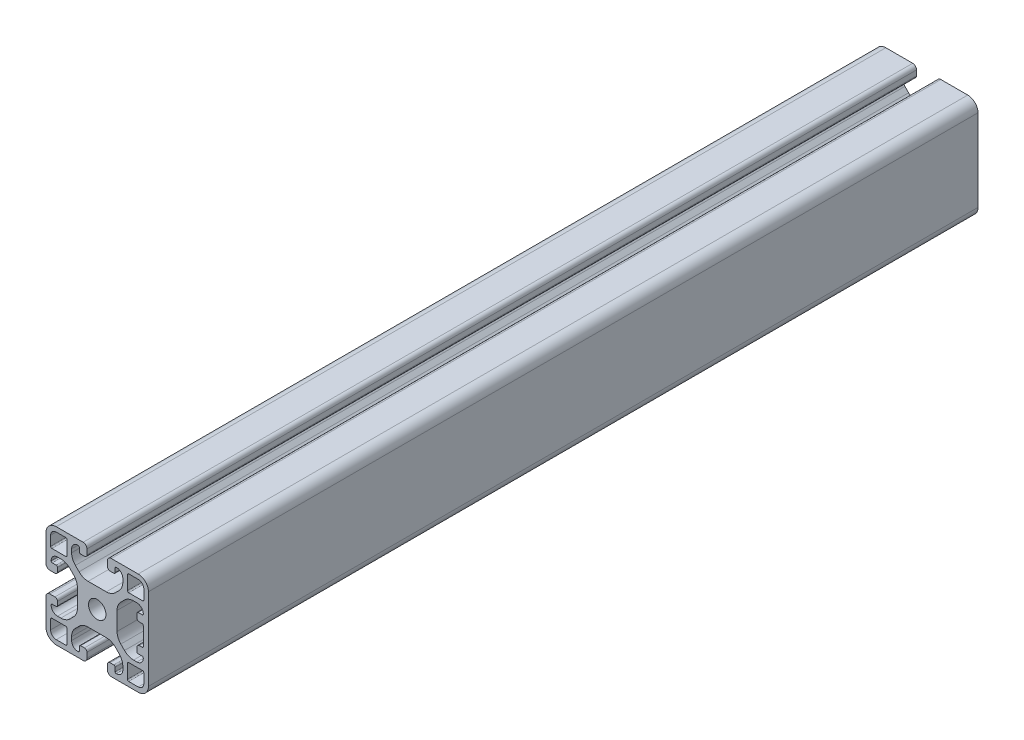
SolidWorks part; units mm, degrees
ref_plane "Piano frontale" through (0, 0, 0) normal (0, 0, 1) x (1, 0, 0)
ref_plane "Piano superiore" through (0, 0, 0) normal (0, 1, 0) x (1, 0, 0)
ref_plane "Piano destro" through (0, 0, 0) normal (1, 0, 0) x (0, 0, -1)
ref_plane "Piano1" through (0, 0, -340) normal (0, 0, -1) x (-1, 0, 0)
sketch "Schizzo1" plane through (0, 0, -340) normal (0, 0, -1) x (-1, 0, 0)
  line L0 (-12.3, -18.2) -> (-16, -18.2)
  line L1 (-18.2, -16) -> (-18.2, -12.3)
  line L2 (-17.7, -11.8) -> (-12.3, -11.8)
  line L3 (-11.8, -12.3) -> (-11.8, -17.7)
  line L4 (-11.8, 17.7) -> (-11.8, 12.3)
  line L5 (-12.3, 11.8) -> (-17.7, 11.8)
  line L6 (-18.2, 12.3) -> (-18.2, 16)
  line L7 (-16, 18.2) -> (-12.3, 18.2)
  line L8 (18.2, 16) -> (18.2, 12.3)
  line L9 (17.7, 11.8) -> (12.3, 11.8)
  line L10 (11.8, 12.3) -> (11.8, 17.7)
  line L11 (12.3, 18.2) -> (16, 18.2)
  line L12 (6.5, -15.5) -> (5, -15.5)
  line L13 (4, -16.5) -> (4, -18.5)
  line L14 (5.5, -20) -> (16, -20)
  line L15 (20, -16) -> (20, -5.5)
  line L16 (18.5, -4) -> (16.5, -4)
  line L17 (15.5, -5) -> (15.5, -6.5)
  line L18 (16, -7) -> (17.55, -7)
  line L19 (18, -7.45) -> (18, -7.5)
  line L20 (15.5, -10) -> (14.1924, -10)
  line L21 (10.6569, -8.5355) -> (9.2145, -7.0931)
  line L22 (7.75, -3.5576) -> (7.75, 3.5576)
  line L23 (9.2145, 7.0931) -> (10.6569, 8.5355)
  line L24 (14.1924, 10) -> (15.5, 10)
  line L25 (18, 7.5) -> (18, 7.45)
  line L26 (17.55, 7) -> (16, 7)
  line L27 (15.5, 6.5) -> (15.5, 5)
  line L28 (16.5, 4) -> (18.5, 4)
  line L29 (20, 5.5) -> (20, 16)
  line L30 (16, 20) -> (5.5, 20)
  line L31 (4, 18.5) -> (4, 16.5)
  line L32 (5, 15.5) -> (6.5, 15.5)
  line L33 (7, 16) -> (7, 17.55)
  line L34 (7.45, 18) -> (7.5, 18)
  line L35 (10, 15.5) -> (10, 14.1924)
  line L36 (8.5355, 10.6569) -> (7.0931, 9.2145)
  line L37 (3.5576, 7.75) -> (-3.5576, 7.75)
  line L38 (-7.0931, 9.2145) -> (-8.5355, 10.6569)
  line L39 (-10, 14.1924) -> (-10, 15.5)
  line L40 (-7.5, 18) -> (-7.45, 18)
  line L41 (-7, 17.55) -> (-7, 16)
  line L42 (-6.5, 15.5) -> (-5, 15.5)
  line L43 (-4, 16.5) -> (-4, 18.5)
  line L44 (-5.5, 20) -> (-16, 20)
  line L45 (-20, 16) -> (-20, -16)
  line L46 (-16, -20) -> (-5.5, -20)
  line L47 (-4, -18.5) -> (-4, -16.5)
  line L48 (-5, -15.5) -> (-6.5, -15.5)
  line L49 (-7, -16) -> (-7, -17.55)
  line L50 (-7.45, -18) -> (-7.5, -18)
  line L51 (-10, -15.5) -> (-10, -14.1924)
  line L52 (-8.5355, -10.6569) -> (-7.0931, -9.2145)
  line L53 (-3.5576, -7.75) -> (3.5576, -7.75)
  line L54 (7.0931, -9.2145) -> (8.5355, -10.6569)
  line L55 (10, -14.1924) -> (10, -15.5)
  line L56 (7.5, -18) -> (7.45, -18)
  line L57 (7, -17.55) -> (7, -16)
  line L58 (18.2, -12.3) -> (18.2, -16)
  line L59 (16, -18.2) -> (12.3, -18.2)
  line L60 (11.8, -17.7) -> (11.8, -12.3)
  line L61 (12.3, -11.8) -> (17.7, -11.8)
  line L62 (-16, 7) -> (-17.5, 7)
  line L63 (-15.5, 10) -> (-14.1924, 10)
  line L64 (-10.6569, 8.5355) -> (-9.2145, 7.0931)
  line L65 (-7.75, 3.5576) -> (-7.75, -3.5576)
  line L66 (-9.2145, -7.0931) -> (-10.6569, -8.5355)
  line L67 (-14.1924, -10) -> (-15.5, -10)
  line L68 (-17.5, -7) -> (-16, -7)
  line L69 (-15.5, -6.5) -> (-15.5, -5)
  line L70 (-16.5, -4) -> (-17.5, -4)
  line L71 (-18, -3.5) -> (-18, 3.5)
  line L72 (-17.5, 4) -> (-16.5, 4)
  line L73 (-15.5, 5) -> (-15.5, 6.5)
  arc A0 (-16, -18.2) -> (-18.2, -16) centre (-16, -16) cw
  arc A1 (-18.2, -12.3) -> (-17.7, -11.8) centre (-17.7, -12.3) cw
  arc A2 (-12.3, -11.8) -> (-11.8, -12.3) centre (-12.3, -12.3) cw
  arc A3 (-11.8, -17.7) -> (-12.3, -18.2) centre (-12.3, -17.7) cw
  arc A4 (-12.3, 18.2) -> (-11.8, 17.7) centre (-12.3, 17.7) cw
  arc A5 (-11.8, 12.3) -> (-12.3, 11.8) centre (-12.3, 12.3) cw
  arc A6 (-17.7, 11.8) -> (-18.2, 12.3) centre (-17.7, 12.3) cw
  arc A7 (-18.2, 16) -> (-16, 18.2) centre (-16, 16) cw
  arc A8 (16, 18.2) -> (18.2, 16) centre (16, 16) cw
  arc A9 (18.2, 12.3) -> (17.7, 11.8) centre (17.7, 12.3) cw
  arc A10 (12.3, 11.8) -> (11.8, 12.3) centre (12.3, 12.3) cw
  arc A11 (11.8, 17.7) -> (12.3, 18.2) centre (12.3, 17.7) cw
  arc A12 (5, -15.5) -> (4, -16.5) centre (5, -16.5) ccw
  arc A13 (4, -18.5) -> (5.5, -20) centre (5.5, -18.5) ccw
  arc A14 (16, -20) -> (20, -16) centre (16, -16) ccw
  arc A15 (20, -5.5) -> (18.5, -4) centre (18.5, -5.5) ccw
  arc A16 (16.5, -4) -> (15.5, -5) centre (16.5, -5) ccw
  arc A17 (15.5, -6.5) -> (16, -7) centre (16, -6.5) ccw
  arc A18 (17.55, -7) -> (18, -7.45) centre (17.55, -7.45) cw
  arc A19 (18, -7.5) -> (15.5, -10) centre (15.5, -7.5) cw
  arc A20 (14.1924, -10) -> (10.6569, -8.5355) centre (14.1924, -5) cw
  arc A21 (9.2145, -7.0931) -> (7.75, -3.5576) centre (12.75, -3.5576) cw
  arc A22 (7.75, 3.5576) -> (9.2145, 7.0931) centre (12.75, 3.5576) cw
  arc A23 (10.6569, 8.5355) -> (14.1924, 10) centre (14.1924, 5) cw
  arc A24 (15.5, 10) -> (18, 7.5) centre (15.5, 7.5) cw
  arc A25 (18, 7.45) -> (17.55, 7) centre (17.55, 7.45) cw
  arc A26 (16, 7) -> (15.5, 6.5) centre (16, 6.5) ccw
  arc A27 (15.5, 5) -> (16.5, 4) centre (16.5, 5) ccw
  arc A28 (18.5, 4) -> (20, 5.5) centre (18.5, 5.5) ccw
  arc A29 (20, 16) -> (16, 20) centre (16, 16) ccw
  arc A30 (5.5, 20) -> (4, 18.5) centre (5.5, 18.5) ccw
  arc A31 (4, 16.5) -> (5, 15.5) centre (5, 16.5) ccw
  arc A32 (6.5, 15.5) -> (7, 16) centre (6.5, 16) ccw
  arc A33 (7, 17.55) -> (7.45, 18) centre (7.45, 17.55) cw
  arc A34 (7.5, 18) -> (10, 15.5) centre (7.5, 15.5) cw
  arc A35 (10, 14.1924) -> (8.5355, 10.6569) centre (5, 14.1924) cw
  arc A36 (7.0931, 9.2145) -> (3.5576, 7.75) centre (3.5576, 12.75) cw
  arc A37 (-3.5576, 7.75) -> (-7.0931, 9.2145) centre (-3.5576, 12.75) cw
  arc A38 (-8.5355, 10.6569) -> (-10, 14.1924) centre (-5, 14.1924) cw
  arc A39 (-10, 15.5) -> (-7.5, 18) centre (-7.5, 15.5) cw
  arc A40 (-7.45, 18) -> (-7, 17.55) centre (-7.45, 17.55) cw
  arc A41 (-7, 16) -> (-6.5, 15.5) centre (-6.5, 16) ccw
  arc A42 (-5, 15.5) -> (-4, 16.5) centre (-5, 16.5) ccw
  arc A43 (-4, 18.5) -> (-5.5, 20) centre (-5.5, 18.5) ccw
  arc A44 (-16, 20) -> (-20, 16) centre (-16, 16) ccw
  arc A45 (-20, -16) -> (-16, -20) centre (-16, -16) ccw
  arc A46 (-5.5, -20) -> (-4, -18.5) centre (-5.5, -18.5) ccw
  arc A47 (-4, -16.5) -> (-5, -15.5) centre (-5, -16.5) ccw
  arc A48 (-6.5, -15.5) -> (-7, -16) centre (-6.5, -16) ccw
  arc A49 (-7, -17.55) -> (-7.45, -18) centre (-7.45, -17.55) cw
  arc A50 (-7.5, -18) -> (-10, -15.5) centre (-7.5, -15.5) cw
  arc A51 (-10, -14.1924) -> (-8.5355, -10.6569) centre (-5, -14.1924) cw
  arc A52 (-7.0931, -9.2145) -> (-3.5576, -7.75) centre (-3.5576, -12.75) cw
  arc A53 (3.5576, -7.75) -> (7.0931, -9.2145) centre (3.5576, -12.75) cw
  arc A54 (8.5355, -10.6569) -> (10, -14.1924) centre (5, -14.1924) cw
  arc A55 (10, -15.5) -> (7.5, -18) centre (7.5, -15.5) cw
  arc A56 (7.45, -18) -> (7, -17.55) centre (7.45, -17.55) cw
  arc A57 (7, -16) -> (6.5, -15.5) centre (6.5, -16) ccw
  arc A58 (17.7, -11.8) -> (18.2, -12.3) centre (17.7, -12.3) cw
  arc A59 (18.2, -16) -> (16, -18.2) centre (16, -16) cw
  arc A60 (12.3, -18.2) -> (11.8, -17.7) centre (12.3, -17.7) cw
  arc A61 (11.8, -12.3) -> (12.3, -11.8) centre (12.3, -12.3) cw
  circle A62 centre (0, 0) radius 3.4
  arc A63 (-15.5, 6.5) -> (-16, 7) centre (-16, 6.5) ccw
  arc A64 (-17.5, 7) -> (-18, 7.5) centre (-17.5, 7.5) cw
  arc A65 (-18, 7.5) -> (-15.5, 10) centre (-15.5, 7.5) cw
  arc A66 (-14.1924, 10) -> (-10.6569, 8.5355) centre (-14.1924, 5) cw
  arc A67 (-9.2145, 7.0931) -> (-7.75, 3.5576) centre (-12.75, 3.5576) cw
  arc A68 (-7.75, -3.5576) -> (-9.2145, -7.0931) centre (-12.75, -3.5576) cw
  arc A69 (-10.6569, -8.5355) -> (-14.1924, -10) centre (-14.1924, -5) cw
  arc A70 (-15.5, -10) -> (-18, -7.5) centre (-15.5, -7.5) cw
  arc A71 (-18, -7.5) -> (-17.5, -7) centre (-17.5, -7.5) cw
  arc A72 (-16, -7) -> (-15.5, -6.5) centre (-16, -6.5) ccw
  arc A73 (-15.5, -5) -> (-16.5, -4) centre (-16.5, -5) ccw
  arc A74 (-17.5, -4) -> (-18, -3.5) centre (-17.5, -3.5) cw
  arc A75 (-18, 3.5) -> (-17.5, 4) centre (-17.5, 3.5) cw
  arc A76 (-16.5, 4) -> (-15.5, 5) centre (-16.5, 5) ccw
extrude "Estrusione-Estrusione1" add sketch "Schizzo1" against normal blind 324
